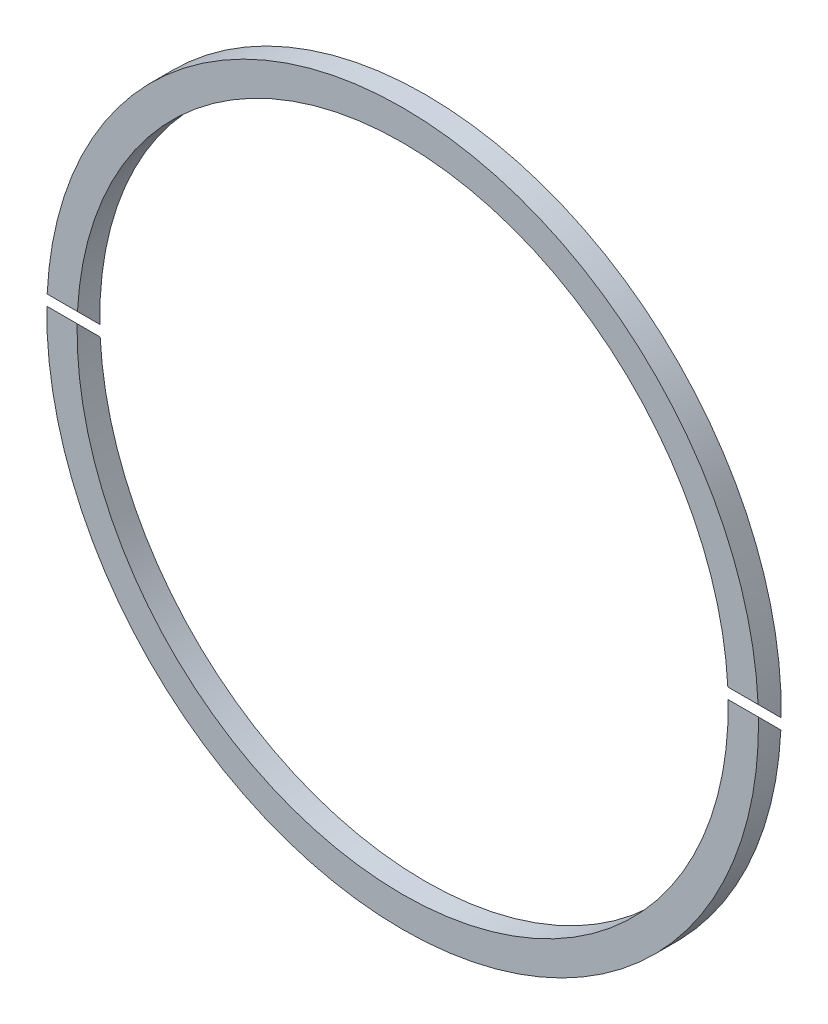
SolidWorks part; units mm, degrees
ref_plane "Front Plane" through (0, 0, 0) normal (0, 0, 1) x (1, 0, 0)
ref_plane "Top Plane" through (0, 0, 0) normal (0, 1, 0) x (1, 0, 0)
ref_plane "Right Plane" through (0, 0, 0) normal (1, 0, 0) x (0, 0, -1)
sketch "Sketch1" plane through (0, 0, 0) normal (0, 0, 1) x (1, 0, 0)
  circle A0 centre (0, 0) radius 47
  circle A1 centre (0, 0) radius 43
  dimension "D1" = 86
  dimension "D2" = 94
extrude "Boss-Extrude1" add sketch "Sketch1" along normal mid plane 3
sketch "Sketch2" plane through (0, 0, 0) normal (1, 0, 0) x (0, 0, -1)
  line L0 (-4.0653, 3.3582) -> (5.8136, -6.5207)
  line L1 (5.8136, -6.5207) -> (6.5207, -5.8136)
  line L2 (6.5207, -5.8136) -> (-3.3582, 4.0653)
  line L3 (-3.3582, 4.0653) -> (-4.0653, 3.3582)
  line L4 (0, 0) -> (2.4739, -2.4739) construction
  line L5 (0, 0) -> (0, 2.8844) construction
  dimension "D1" = 0.5
  dimension "D2" = 0.5
  dimension "D3" = 135
extrude "Cut-Extrude2" cut sketch "Sketch2" against normal through all both and the other way through all contours L3 L0 L1 L2
